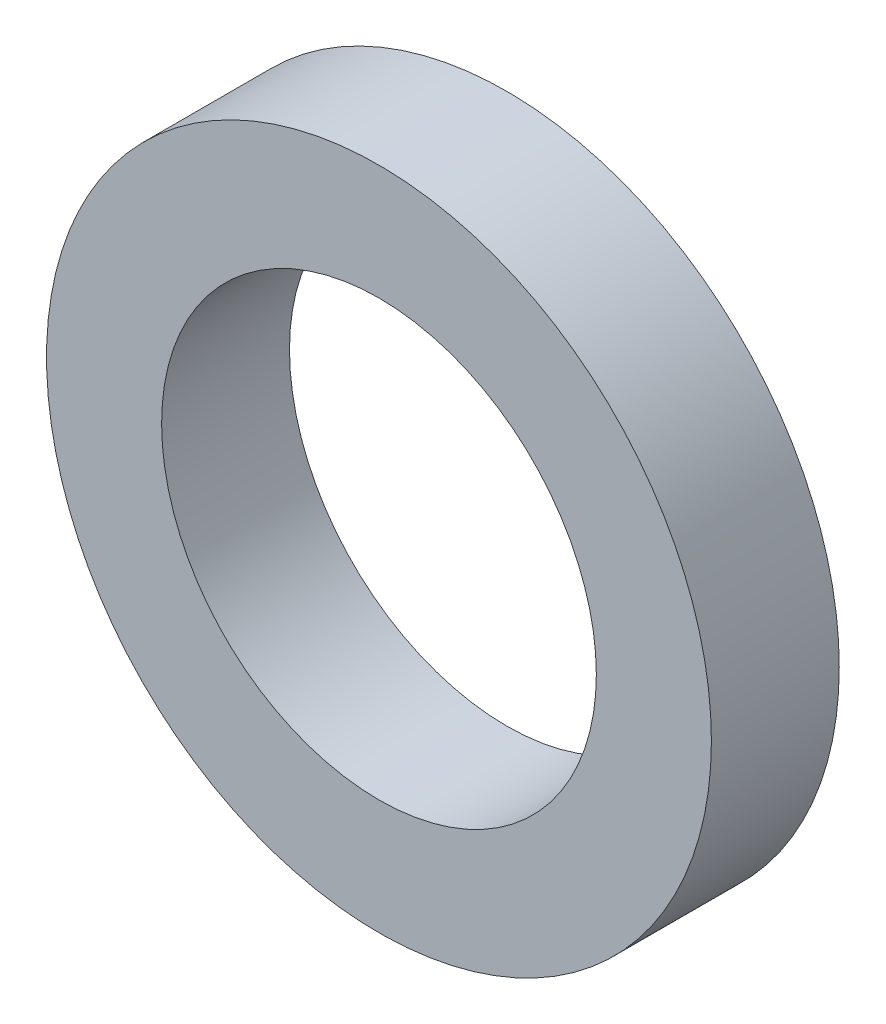
SolidWorks part; units mm, degrees
material "Chrome Stainless Steel"
ref_plane "Front Plane" through (0, 0, 0) normal (0, 0, 1) x (1, 0, 0)
ref_plane "Top Plane" through (0, 0, 0) normal (0, 1, 0) x (1, 0, 0)
ref_plane "Right Plane" through (0, 0, 0) normal (1, 0, 0) x (0, 0, -1)
sketch "Sketch1" plane through (0, 0, 0) normal (0, 0, 1) x (1, 0, 0)
  circle A0 centre (0, 0) radius 8.5
  circle A1 centre (0, 0) radius 13
  dimension "D1" = 17
  dimension "D2" = 26
extrude "Boss-Extrude1" add sketch "Sketch1" along normal blind 5
